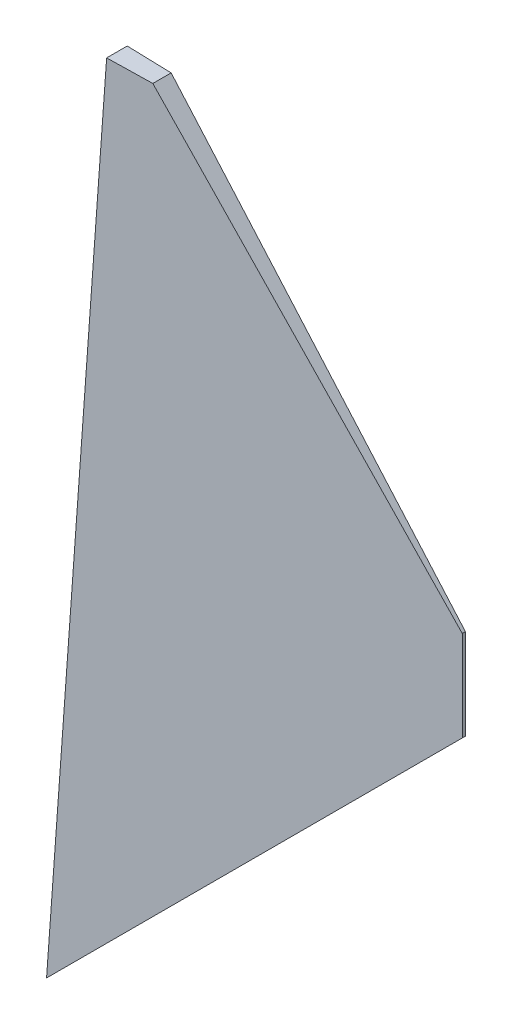
SolidWorks part; units mm, degrees
ref_plane "Front Plane" through (0, 0, 0) normal (0, 0, 1) x (1, 0, 0)
ref_plane "Top Plane" through (0, 0, 0) normal (0, 1, 0) x (1, 0, 0)
ref_plane "Right Plane" through (0, 0, 0) normal (1, 0, 0) x (0, 0, -1)
sketch "Sketch1" plane through (0, 0, 0) normal (0, 1, 0) x (1, 0, 0)
  line L0 (0, -3.9372) -> (0, 9.2708)
  line L1 (228.6, 2.6668) -> (228.6, 0.8888)
  line L2 (0, 9.2708) -> (228.6, 2.6668)
  line L3 (228.6, 0.8888) -> (0, -3.9372)
  dimension "D1" = 13.208
  dimension "D2" = 1.778
  dimension "D3" = 228.6
  dimension "D4" = 6.604
extrude "Boss-Extrude1" add sketch "Sketch1" along normal blind 508
sketch "Sketch3" plane through (0, 0, 0) normal (0, 0, 1) x (1, 0, 0)
  line L0 (0, 0) -> (151.3, 151.3)
  line L1 (151.3, 151.3) -> (228.6, 228.6)
  line L2 (228.6, 508) -> (228.6, 0) construction
  line L4 (228.6, 279.4) -> (58.437, 463.5962)
  line L5 (58.437, 463.5962) -> (33.037, 463.5962)
  line L6 (33.037, 463.5962) -> (0, 0)
  line L7 (0, 0) -> (0, 508)
  line L8 (0, 508) -> (228.6, 508)
  line L9 (228.6, 508) -> (228.6, 279.4)
  line L10 (228.6, 228.6) -> (228.6, 0)
  line L11 (228.6, 0) -> (0, 0)
  dimension "D1" = 25.4
  dimension "D2" = 250.7662
  dimension "D3" = 50.8
  dimension "D4" = 464.7718
extrude "Cut-Extrude3" cut sketch "Sketch3" against normal through all both and the other way through all contours L11 L10 L1 L0 | L9 L8 L7 L6 L5 L4
